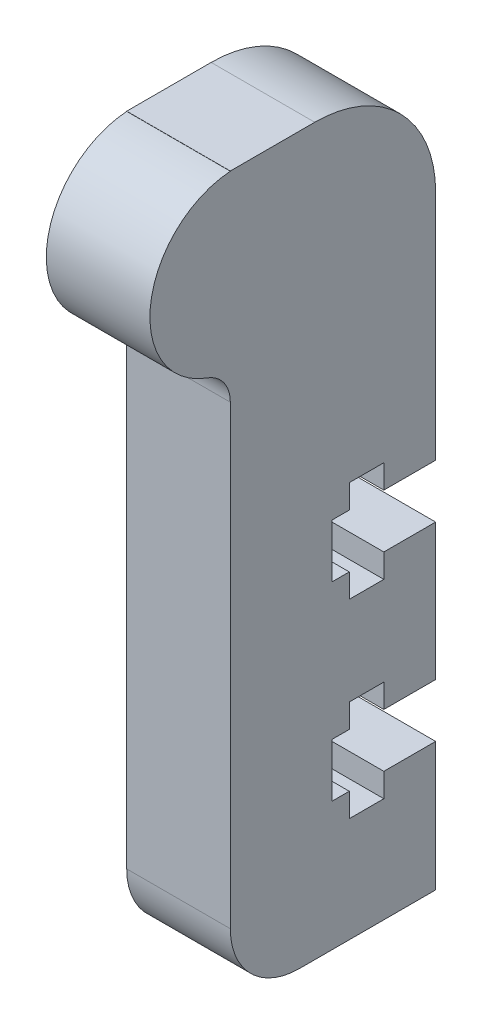
SolidWorks part; units mm, degrees
ref_plane "Płaszczyzna przednia" through (0, 0, 0) normal (0, 0, 1) x (1, 0, 0)
ref_plane "Płaszczyzna górna" through (0, 0, 0) normal (0, 1, 0) x (1, 0, 0)
ref_plane "Płaszczyzna prawa" through (0, 0, 0) normal (1, 0, 0) x (0, 0, -1)
sketch "Szkic8" plane through (-151.25, 2.4638, 0) normal (1, 0, 0) x (0, 0, -1)
  line L0 (0, 53.2317) -> (0, 88.2317)
  line L2 (-11.8893, 57.2317) -> (-11.8893, 83.6356)
  line L59 (-7, 95.2317) -> (-11.8901, 95.2317)
  line L60 (-11.8901, 95.2317) -> (-11.8893, 95.2199)
  line L62 (-7.8893, 53.2317) -> (0, 53.2317)
  arc A0 (-11.8893, 83.6356) -> (-13.2198, 85.5202) centre (-13.8893, 83.6356) ccw
  arc A1 (-7.8893, 53.2317) -> (-11.8893, 57.2317) centre (-7.8893, 57.2317) cw
  arc A4 (0, 88.2317) -> (-7, 95.2317) centre (-7, 88.2317) ccw
  arc A5 (-11.8893, 95.2199) -> (-13.2198, 85.5202) centre (-11.5461, 90.2317) ccw
  dimension "D1" = 2
  dimension "D2" = 4
  dimension "D3" = 5
  dimension "D4" = 7
  dimension "D5" = 42
extrude "Dodanie-wyciągnięcie5" add sketch "Szkic8" along normal blind 6
sketch "Szkic2" plane through (-151.25, 155.6074, 0) normal (-1, 0, 0) x (0, 0, -1)
  line L0 (-6, 81.4619) -> (-6, 78.3619)
  line L1 (-6, 81.4619) -> (-5, 81.4619)
  line L2 (-6, 78.3619) -> (-5, 78.3619)
  line L3 (0, 81.4619) -> (0, 78.3619)
  line L5 (-3, 82.8369) -> (-5, 82.8369)
  line L6 (-3, 82.8369) -> (-3, 81.4619)
  line L7 (-5, 82.8369) -> (-5, 81.4619)
  line L8 (-3, 76.9869) -> (-5, 76.9869)
  line L9 (-3, 78.3619) -> (-3, 76.9869)
  line L10 (-3, 78.3619) -> (0, 78.3619)
  line L11 (-5, 78.3619) -> (-5, 76.9869)
  line L12 (-3, 81.4619) -> (0, 81.4619)
  line L14 (-7, 57.9119) -> (-11.8901, 57.9119) construction
  line L15 (0, 99.9119) -> (0, 64.9119) construction
  point P14 (-6, 79.9119)
  dimension "D1" = 6
  dimension "D2" = 1
  dimension "D3" = 2
  dimension "D4" = 5.85
  dimension "D5" = 3.1
  dimension "D6" = 1.375
  dimension "D7" = 22
  dimension "D8" = 0
extrude "Wytnij-wyciągnięcie1" cut sketch "Szkic2" against normal blind 20
pattern_linear "Szyk liniowy1" count 2 spacing 11 along (0, -1, 0) of "Wytnij-wyciągnięcie1"
equation "\"tolerancja_wpusy\"=0.2"
equation "\"dlugosc_wpustu_duzy\"=20"
equation "\"srednica_otworu_M3\"=3.1"
equation "\"szerokosc_nogi_T\"=3.1"
equation "\"dlugosc_T_30\"=11"
equation "\"grubosc_na_nakretke_kwadrat\"=2"
equation "\"szerokosc_na_nakretke_kwadrat\"=5.85"
equation "\"wyokosc_nadstawki_T\"=0.5"
equation "\"dlugosc_T_20_6\"=14"
equation "\"D3@Szkic2\"=\"grubosc_na_nakretke_kwadrat\""
equation "\"D4@Szkic2\"=\"szerokosc_na_nakretke_kwadrat\""
equation "\"D5@Szkic2\"=\"szerokosc_nogi_T\""
equation "\"D6@Szkic2\"=(\"szerokosc_na_nakretke_kwadrat\"-\"szerokosc_nogi_T\")/2"
